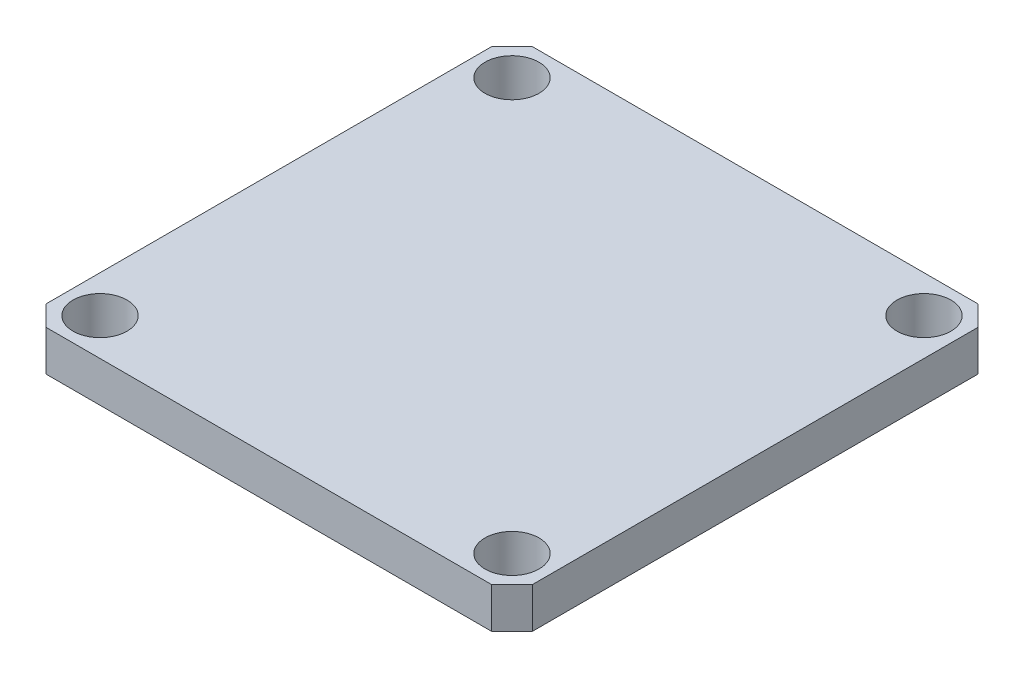
SolidWorks part; units mm, degrees
ref_plane "前视基准面" through (0, 0, 0) normal (0, 0, 1) x (1, 0, 0)
ref_plane "上视基准面" through (0, 0, 0) normal (0, 1, 0) x (1, 0, 0)
ref_plane "右视基准面" through (0, 0, 0) normal (1, 0, 0) x (0, 0, -1)
other "Configuration Table"
sketch "草图1" plane through (0, 0, 0) normal (0, 1, 0) x (1, 0, 0)
  line L0 (-16.5, -18) -> (16.5, -18)
  line L1 (16.5, -18) -> (18, -16.5)
  line L2 (18, -16.5) -> (18, 16.5)
  line L3 (18, 16.5) -> (16.5, 18)
  line L4 (16.5, 18) -> (-16.5, 18)
  line L5 (-16.5, 18) -> (-18, 16.5)
  line L6 (-18, 16.5) -> (-18, -16.5)
  line L7 (-18, -16.5) -> (-16.5, -18)
  line L8 (0, 0) -> (26.8206, 0) construction
  line L9 (0, 0) -> (0, -11.0817) construction
  circle A0 centre (15.25, 15.25) radius 2
  circle A1 centre (-15.25, 15.25) radius 2
  circle A2 centre (15.25, -15.25) radius 2
  circle A3 centre (-15.25, -15.25) radius 2
  dimension "D2" = 4
  dimension "D1" = 33
  dimension "D3" = 15.25
  dimension "D4" = 15.25
extrude "凸台-拉伸1" add sketch "草图1" along normal blind 3
